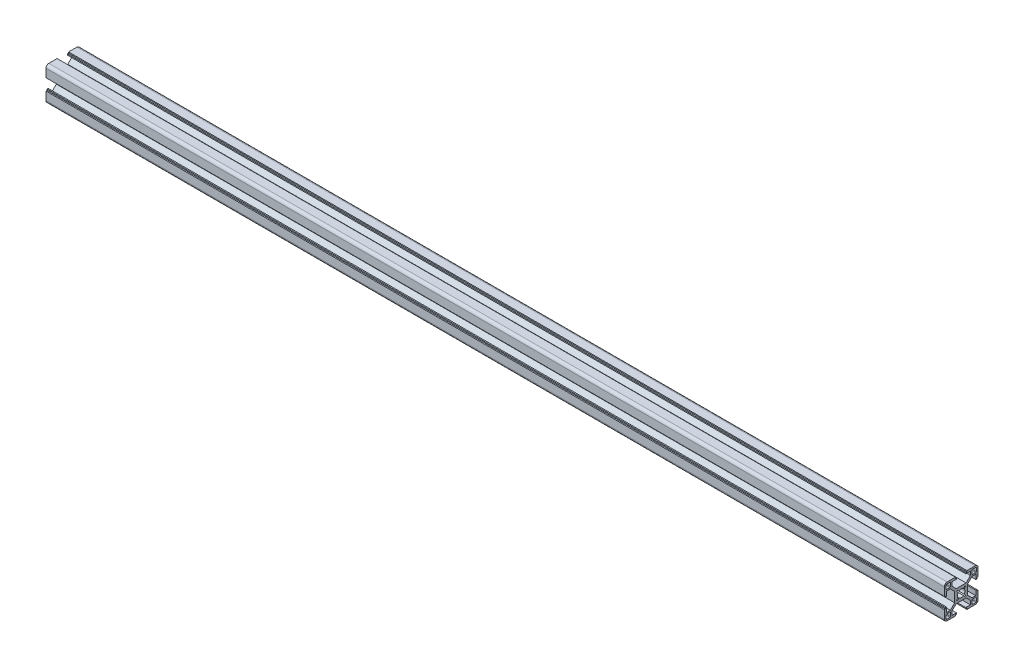
SolidWorks part; units mm, degrees
ref_plane "前视基准面" through (0, 0, 0) normal (0, 0, 1) x (1, 0, 0)
ref_plane "上视基准面" through (0, 0, 0) normal (0, 1, 0) x (1, 0, 0)
ref_plane "右视基准面" through (0, 0, 0) normal (1, 0, 0) x (0, 0, -1)
other "Configuration Table"
sketch "草图1" plane through (0, 0, 0) normal (1, 0, 0) x (0, 0, -1)
  line L0 (-5.1496, -13.7047) -> (-4.1496, -13.7047)
  line L1 (-4.1496, -13.7047) -> (-4.1496, -12.7047)
  line L2 (-4.1496, -12.7047) -> (-8.2996, -12.7047)
  line L3 (-8.2996, -12.7047) -> (-8.2996, -9.3689)
  line L4 (-8.2996, -9.3689) -> (-4.4354, -5.5047)
  line L5 (-4.4354, -5.5047) -> (4.3362, -5.5047)
  line L6 (4.3362, -5.5047) -> (8.2004, -9.3689)
  line L7 (8.2004, -9.3689) -> (8.2004, -12.7047)
  line L8 (8.2004, -12.7047) -> (4.0504, -12.7047)
  line L9 (4.0504, -12.7047) -> (4.0504, -13.7047)
  line L10 (4.0504, -13.7047) -> (5.0504, -13.7047)
  line L11 (5.0504, -13.7047) -> (5.0504, -14.7047)
  line L12 (5.0504, -14.7047) -> (12.4504, -14.7047)
  line L13 (14.9504, -12.2047) -> (14.9504, -4.8047)
  line L14 (14.9504, -4.8047) -> (13.9504, -4.8047)
  line L15 (13.9504, -4.8047) -> (13.9504, -3.8047)
  line L16 (13.9504, -3.8047) -> (12.9504, -3.8047)
  line L17 (12.9504, -3.8047) -> (12.9504, -7.9547)
  line L18 (12.9504, -7.9547) -> (9.6146, -7.9547)
  line L19 (9.6146, -7.9547) -> (5.7504, -4.0905)
  line L20 (5.7504, -4.0905) -> (5.7504, 4.6811)
  line L21 (5.7504, 4.6811) -> (9.6146, 8.5453)
  line L22 (9.6146, 8.5453) -> (12.9504, 8.5453)
  line L23 (12.9504, 8.5453) -> (12.9504, 4.3953)
  line L24 (12.9504, 4.3953) -> (13.9504, 4.3953)
  line L25 (13.9504, 4.3953) -> (13.9504, 5.3953)
  line L26 (13.9504, 5.3953) -> (14.9504, 5.3953)
  line L27 (14.9504, 5.3953) -> (14.9504, 12.7953)
  line L28 (12.4504, 15.2953) -> (5.0504, 15.2953)
  line L29 (5.0504, 15.2953) -> (5.0504, 14.2953)
  line L30 (5.0504, 14.2953) -> (4.0504, 14.2953)
  line L31 (4.0504, 14.2953) -> (4.0504, 13.2953)
  line L32 (4.0504, 13.2953) -> (8.2004, 13.2953)
  line L33 (8.2004, 13.2953) -> (8.2004, 9.9595)
  line L34 (8.2004, 9.9595) -> (4.3362, 6.0953)
  line L35 (4.3362, 6.0953) -> (-4.4354, 6.0953)
  line L36 (-4.4354, 6.0953) -> (-8.2996, 9.9595)
  line L37 (-8.2996, 9.9595) -> (-8.2996, 13.2953)
  line L38 (-8.2996, 13.2953) -> (-4.1496, 13.2953)
  line L39 (-4.1496, 13.2953) -> (-4.1496, 14.2953)
  line L40 (-4.1496, 14.2953) -> (-5.1496, 14.2953)
  line L41 (-5.1496, 14.2953) -> (-5.1496, 15.2953)
  line L42 (-5.1496, 15.2953) -> (-12.5496, 15.2953)
  line L43 (-15.0496, 12.7953) -> (-15.0496, 5.3953)
  line L44 (-15.0496, 5.3953) -> (-14.0496, 5.3953)
  line L45 (-14.0496, 5.3953) -> (-14.0496, 4.3953)
  line L46 (-14.0496, 4.3953) -> (-13.0496, 4.3953)
  line L47 (-13.0496, 4.3953) -> (-13.0496, 8.5453)
  line L48 (-13.0496, 8.5453) -> (-9.7138, 8.5453)
  line L49 (-9.7138, 8.5453) -> (-5.8496, 4.6811)
  line L50 (-5.8496, 4.6811) -> (-5.8496, -4.0905)
  line L51 (-5.8496, -4.0905) -> (-9.7138, -7.9547)
  line L52 (-9.7138, -7.9547) -> (-13.0496, -7.9547)
  line L53 (-13.0496, -7.9547) -> (-13.0496, -3.8047)
  line L54 (-13.0496, -3.8047) -> (-14.0496, -3.8047)
  line L55 (-14.0496, -3.8047) -> (-14.0496, -4.8047)
  line L56 (-14.0496, -4.8047) -> (-15.0496, -4.8047)
  line L57 (-15.0496, -4.8047) -> (-15.0496, -12.2047)
  line L58 (-12.5496, -14.7047) -> (-5.1496, -14.7047)
  line L59 (-5.1496, -14.7047) -> (-5.1496, -13.7047)
  line L60 (-10.0496, 9.7953) -> (-13.0496, 9.7953)
  line L61 (-13.5496, 10.2953) -> (-13.5496, 13.2953)
  line L62 (-13.0496, 13.7953) -> (-10.0496, 13.7953)
  line L63 (-9.5496, 13.2953) -> (-9.5496, 10.2953)
  line L64 (-10.0496, -13.2047) -> (-13.0496, -13.2047)
  line L65 (-13.5496, -12.7047) -> (-13.5496, -9.7047)
  line L66 (-13.0496, -9.2047) -> (-10.0496, -9.2047)
  line L67 (-9.5496, -9.7047) -> (-9.5496, -12.7047)
  line L68 (12.9504, 9.7953) -> (9.9504, 9.7953)
  line L69 (9.4504, 10.2953) -> (9.4504, 13.2953)
  line L70 (9.9504, 13.7953) -> (12.9504, 13.7953)
  line L71 (13.4504, 13.2953) -> (13.4504, 10.2953)
  line L72 (13.4504, -9.7047) -> (13.4504, -12.7047)
  line L73 (12.9504, -13.2047) -> (9.9504, -13.2047)
  line L74 (9.4504, -12.7047) -> (9.4504, -9.7047)
  line L75 (9.9504, -9.2047) -> (12.9504, -9.2047)
  line L76 (-4.08, 3.6186) -> (-3.3729, 4.3257)
  line L77 (-3.3729, 4.3257) -> (-2.074, 3.0269)
  line L78 (1.9749, 3.0269) -> (3.2737, 4.3257)
  line L79 (3.2737, 4.3257) -> (3.9808, 3.6186)
  line L80 (3.9808, 3.6186) -> (2.682, 2.3198)
  line L81 (2.682, -1.7291) -> (3.9808, -3.028)
  line L82 (3.9808, -3.028) -> (3.2737, -3.7351)
  line L83 (3.2737, -3.7351) -> (1.9749, -2.4362)
  line L84 (-2.074, -2.4362) -> (-3.3729, -3.7351)
  line L85 (-3.3729, -3.7351) -> (-4.08, -3.028)
  line L86 (-4.08, -3.028) -> (-2.7811, -1.7291)
  line L87 (-2.7811, 2.3198) -> (-4.08, 3.6186)
  arc A0 (12.4504, -14.7047) -> (14.9504, -12.2047) centre (12.4504, -12.2047) ccw
  arc A1 (14.9504, 12.7953) -> (12.4504, 15.2953) centre (12.4504, 12.7953) ccw
  arc A2 (-12.5496, 15.2953) -> (-15.0496, 12.7953) centre (-12.5496, 12.7953) ccw
  arc A3 (-15.0496, -12.2047) -> (-12.5496, -14.7047) centre (-12.5496, -12.2047) ccw
  arc A4 (-9.5496, 10.2953) -> (-10.0496, 9.7953) centre (-10.0496, 10.2953) cw
  arc A5 (-13.0496, 9.7953) -> (-13.5496, 10.2953) centre (-13.0496, 10.2953) cw
  arc A6 (-13.5496, 13.2953) -> (-13.0496, 13.7953) centre (-13.0496, 13.2953) cw
  arc A7 (-10.0496, 13.7953) -> (-9.5496, 13.2953) centre (-10.0496, 13.2953) cw
  arc A8 (-9.5496, -12.7047) -> (-10.0496, -13.2047) centre (-10.0496, -12.7047) cw
  arc A9 (-13.0496, -13.2047) -> (-13.5496, -12.7047) centre (-13.0496, -12.7047) cw
  arc A10 (-13.5496, -9.7047) -> (-13.0496, -9.2047) centre (-13.0496, -9.7047) cw
  arc A11 (-10.0496, -9.2047) -> (-9.5496, -9.7047) centre (-10.0496, -9.7047) cw
  arc A12 (13.4504, 10.2953) -> (12.9504, 9.7953) centre (12.9504, 10.2953) cw
  arc A13 (9.9504, 9.7953) -> (9.4504, 10.2953) centre (9.9504, 10.2953) cw
  arc A14 (9.4504, 13.2953) -> (9.9504, 13.7953) centre (9.9504, 13.2953) cw
  arc A15 (12.9504, 13.7953) -> (13.4504, 13.2953) centre (12.9504, 13.2953) cw
  arc A16 (12.9504, -9.2047) -> (13.4504, -9.7047) centre (12.9504, -9.7047) cw
  arc A17 (13.4504, -12.7047) -> (12.9504, -13.2047) centre (12.9504, -12.7047) cw
  arc A18 (9.9504, -13.2047) -> (9.4504, -12.7047) centre (9.9504, -12.7047) cw
  arc A19 (9.4504, -9.7047) -> (9.9504, -9.2047) centre (9.9504, -9.7047) cw
  arc A20 (-2.074, 3.0269) -> (1.9749, 3.0269) centre (-0.0496, 0.2953) cw
  arc A21 (2.682, 2.3198) -> (2.682, -1.7291) centre (-0.0496, 0.2953) cw
  arc A22 (1.9749, -2.4362) -> (-2.074, -2.4362) centre (-0.0496, 0.2953) cw
  arc A23 (-2.7811, -1.7291) -> (-2.7811, 2.3198) centre (-0.0496, 0.2953) cw
extrude "凸台-拉伸1" add sketch "草图1" against normal blind 50
sketch "草图2" plane through (0, 0, 0) normal (1, 0, 0) x (0, 0, -1)
  line L4 (-13.0496, 9.7953) -> (-10.0496, 9.7953)
  line L5 (-13.5496, 13.2953) -> (-13.5496, 10.2953)
  line L6 (-10.0496, 13.7953) -> (-13.0496, 13.7953)
  line L7 (-9.5496, 10.2953) -> (-9.5496, 13.2953)
  line L8 (-13.0496, 9.7953) -> (-10.0496, 9.7953)
  line L9 (-13.5496, 13.2953) -> (-13.5496, 10.2953)
  line L10 (-10.0496, 13.7953) -> (-13.0496, 13.7953)
  line L11 (-9.5496, 10.2953) -> (-9.5496, 13.2953)
  line L12 (-13.0496, -13.2047) -> (-10.0496, -13.2047)
  line L13 (-13.5496, -9.7047) -> (-13.5496, -12.7047)
  line L14 (-10.0496, -9.2047) -> (-13.0496, -9.2047)
  line L15 (-9.5496, -12.7047) -> (-9.5496, -9.7047)
  line L16 (-13.0496, -13.2047) -> (-10.0496, -13.2047)
  line L17 (-13.5496, -9.7047) -> (-13.5496, -12.7047)
  line L18 (-10.0496, -9.2047) -> (-13.0496, -9.2047)
  line L19 (-9.5496, -12.7047) -> (-9.5496, -9.7047)
  line L20 (9.4504, 13.2953) -> (9.4504, 10.2953)
  line L21 (12.9504, 13.7953) -> (9.9504, 13.7953)
  line L22 (13.4504, 10.2953) -> (13.4504, 13.2953)
  line L23 (9.9504, 9.7953) -> (12.9504, 9.7953)
  line L24 (9.4504, 13.2953) -> (9.4504, 10.2953)
  line L25 (12.9504, 13.7953) -> (9.9504, 13.7953)
  line L26 (13.4504, 10.2953) -> (13.4504, 13.2953)
  line L27 (9.9504, 9.7953) -> (12.9504, 9.7953)
  line L28 (9.4504, -9.7047) -> (9.4504, -12.7047)
  line L29 (12.9504, -9.2047) -> (9.9504, -9.2047)
  line L30 (13.4504, -12.7047) -> (13.4504, -9.7047)
  line L31 (9.9504, -13.2047) -> (12.9504, -13.2047)
  line L32 (9.4504, -9.7047) -> (9.4504, -12.7047)
  line L33 (12.9504, -9.2047) -> (9.9504, -9.2047)
  line L34 (13.4504, -12.7047) -> (13.4504, -9.7047)
  line L35 (9.9504, -13.2047) -> (12.9504, -13.2047)
  line L44 (-3.3729, -3.7351) -> (-2.074, -2.4362)
  line L45 (-4.08, -3.028) -> (-3.3729, -3.7351)
  line L46 (-2.7811, -1.7291) -> (-4.08, -3.028)
  line L47 (-4.08, 3.6186) -> (-2.7811, 2.3198)
  line L48 (-3.3729, 4.3257) -> (-4.08, 3.6186)
  line L49 (-2.074, 3.0269) -> (-3.3729, 4.3257)
  line L50 (3.2737, 4.3257) -> (1.9749, 3.0269)
  line L51 (3.9808, 3.6186) -> (3.2737, 4.3257)
  line L52 (2.682, 2.3198) -> (3.9808, 3.6186)
  line L53 (3.9808, -3.028) -> (2.682, -1.7291)
  line L54 (3.2737, -3.7351) -> (3.9808, -3.028)
  line L55 (1.9749, -2.4362) -> (3.2737, -3.7351)
  line L56 (-3.3729, -3.7351) -> (-2.074, -2.4362)
  line L57 (-4.08, -3.028) -> (-3.3729, -3.7351)
  line L58 (-2.7811, -1.7291) -> (-4.08, -3.028)
  line L59 (-4.08, 3.6186) -> (-2.7811, 2.3198)
  line L60 (-3.3729, 4.3257) -> (-4.08, 3.6186)
  line L61 (-2.074, 3.0269) -> (-3.3729, 4.3257)
  line L62 (3.2737, 4.3257) -> (1.9749, 3.0269)
  line L63 (3.9808, 3.6186) -> (3.2737, 4.3257)
  line L64 (2.682, 2.3198) -> (3.9808, 3.6186)
  line L65 (3.9808, -3.028) -> (2.682, -1.7291)
  line L66 (3.2737, -3.7351) -> (3.9808, -3.028)
  line L67 (1.9749, -2.4362) -> (3.2737, -3.7351)
  line L68 (-15.0496, -4.8047) -> (-15.0496, -12.2047)
  line L69 (-14.0496, -4.8047) -> (-15.0496, -4.8047)
  line L70 (-14.0496, -3.8047) -> (-14.0496, -4.8047)
  line L71 (-13.0496, -3.8047) -> (-14.0496, -3.8047)
  line L72 (-13.0496, -7.9547) -> (-13.0496, -3.8047)
  line L73 (-9.7138, -7.9547) -> (-13.0496, -7.9547)
  line L74 (-5.8496, -4.0905) -> (-9.7138, -7.9547)
  line L75 (-5.8496, 4.6811) -> (-5.8496, -4.0905)
  line L76 (-9.7138, 8.5453) -> (-5.8496, 4.6811)
  line L77 (-13.0496, 8.5453) -> (-9.7138, 8.5453)
  line L78 (-13.0496, 4.3953) -> (-13.0496, 8.5453)
  line L79 (-14.0496, 4.3953) -> (-13.0496, 4.3953)
  line L80 (-14.0496, 5.3953) -> (-14.0496, 4.3953)
  line L81 (-15.0496, 5.3953) -> (-14.0496, 5.3953)
  line L82 (-15.0496, 12.7953) -> (-15.0496, 5.3953)
  line L83 (-5.1496, 15.2953) -> (-12.5496, 15.2953)
  line L84 (-5.1496, 14.2953) -> (-5.1496, 15.2953)
  line L85 (-4.1496, 14.2953) -> (-5.1496, 14.2953)
  line L86 (-4.1496, 13.2953) -> (-4.1496, 14.2953)
  line L87 (-8.2996, 13.2953) -> (-4.1496, 13.2953)
  line L88 (-8.2996, 9.9595) -> (-8.2996, 13.2953)
  line L89 (-4.4354, 6.0953) -> (-8.2996, 9.9595)
  line L90 (4.3362, 6.0953) -> (-4.4354, 6.0953)
  line L91 (8.2004, 9.9595) -> (4.3362, 6.0953)
  line L92 (8.2004, 13.2953) -> (8.2004, 9.9595)
  line L93 (4.0504, 13.2953) -> (8.2004, 13.2953)
  line L94 (4.0504, 14.2953) -> (4.0504, 13.2953)
  line L95 (5.0504, 14.2953) -> (4.0504, 14.2953)
  line L96 (5.0504, 15.2953) -> (5.0504, 14.2953)
  line L97 (12.4504, 15.2953) -> (5.0504, 15.2953)
  line L98 (14.9504, 5.3953) -> (14.9504, 12.7953)
  line L99 (13.9504, 5.3953) -> (14.9504, 5.3953)
  line L100 (13.9504, 4.3953) -> (13.9504, 5.3953)
  line L101 (12.9504, 4.3953) -> (13.9504, 4.3953)
  line L102 (12.9504, 8.5453) -> (12.9504, 4.3953)
  line L103 (9.6146, 8.5453) -> (12.9504, 8.5453)
  line L104 (5.7504, 4.6811) -> (9.6146, 8.5453)
  line L105 (5.7504, -4.0905) -> (5.7504, 4.6811)
  line L106 (9.6146, -7.9547) -> (5.7504, -4.0905)
  line L107 (12.9504, -7.9547) -> (9.6146, -7.9547)
  line L108 (12.9504, -3.8047) -> (12.9504, -7.9547)
  line L109 (13.9504, -3.8047) -> (12.9504, -3.8047)
  line L110 (13.9504, -4.8047) -> (13.9504, -3.8047)
  line L111 (14.9504, -4.8047) -> (13.9504, -4.8047)
  line L112 (14.9504, -12.2047) -> (14.9504, -4.8047)
  line L113 (5.0504, -14.7047) -> (12.4504, -14.7047)
  line L114 (5.0504, -13.7047) -> (5.0504, -14.7047)
  line L115 (4.0504, -13.7047) -> (5.0504, -13.7047)
  line L116 (4.0504, -12.7047) -> (4.0504, -13.7047)
  line L117 (8.2004, -12.7047) -> (4.0504, -12.7047)
  line L118 (8.2004, -9.3689) -> (8.2004, -12.7047)
  line L119 (4.3362, -5.5047) -> (8.2004, -9.3689)
  line L120 (-4.4354, -5.5047) -> (4.3362, -5.5047)
  line L121 (-8.2996, -9.3689) -> (-4.4354, -5.5047)
  line L122 (-8.2996, -12.7047) -> (-8.2996, -9.3689)
  line L123 (-4.1496, -12.7047) -> (-8.2996, -12.7047)
  line L124 (-4.1496, -13.7047) -> (-4.1496, -12.7047)
  line L125 (-5.1496, -13.7047) -> (-4.1496, -13.7047)
  line L126 (-5.1496, -14.7047) -> (-5.1496, -13.7047)
  line L127 (-12.5496, -14.7047) -> (-5.1496, -14.7047)
  line L128 (-15.0496, -4.8047) -> (-15.0496, -12.2047)
  line L129 (-14.0496, -4.8047) -> (-15.0496, -4.8047)
  line L130 (-14.0496, -3.8047) -> (-14.0496, -4.8047)
  line L131 (-13.0496, -3.8047) -> (-14.0496, -3.8047)
  line L132 (-13.0496, -7.9547) -> (-13.0496, -3.8047)
  line L133 (-9.7138, -7.9547) -> (-13.0496, -7.9547)
  line L134 (-5.8496, -4.0905) -> (-9.7138, -7.9547)
  line L135 (-5.8496, 4.6811) -> (-5.8496, -4.0905)
  line L136 (-9.7138, 8.5453) -> (-5.8496, 4.6811)
  line L137 (-13.0496, 8.5453) -> (-9.7138, 8.5453)
  line L138 (-13.0496, 4.3953) -> (-13.0496, 8.5453)
  line L139 (-14.0496, 4.3953) -> (-13.0496, 4.3953)
  line L140 (-14.0496, 5.3953) -> (-14.0496, 4.3953)
  line L141 (-15.0496, 5.3953) -> (-14.0496, 5.3953)
  line L142 (-15.0496, 12.7953) -> (-15.0496, 5.3953)
  line L143 (-5.1496, 15.2953) -> (-12.5496, 15.2953)
  line L144 (-5.1496, 14.2953) -> (-5.1496, 15.2953)
  line L145 (-4.1496, 14.2953) -> (-5.1496, 14.2953)
  line L146 (-4.1496, 13.2953) -> (-4.1496, 14.2953)
  line L147 (-8.2996, 13.2953) -> (-4.1496, 13.2953)
  line L148 (-8.2996, 9.9595) -> (-8.2996, 13.2953)
  line L149 (-4.4354, 6.0953) -> (-8.2996, 9.9595)
  line L150 (4.3362, 6.0953) -> (-4.4354, 6.0953)
  line L151 (8.2004, 9.9595) -> (4.3362, 6.0953)
  line L152 (8.2004, 13.2953) -> (8.2004, 9.9595)
  line L153 (4.0504, 13.2953) -> (8.2004, 13.2953)
  line L154 (4.0504, 14.2953) -> (4.0504, 13.2953)
  line L155 (5.0504, 14.2953) -> (4.0504, 14.2953)
  line L156 (5.0504, 15.2953) -> (5.0504, 14.2953)
  line L157 (12.4504, 15.2953) -> (5.0504, 15.2953)
  line L158 (14.9504, 5.3953) -> (14.9504, 12.7953)
  line L159 (13.9504, 5.3953) -> (14.9504, 5.3953)
  line L160 (13.9504, 4.3953) -> (13.9504, 5.3953)
  line L161 (12.9504, 4.3953) -> (13.9504, 4.3953)
  line L162 (12.9504, 8.5453) -> (12.9504, 4.3953)
  line L163 (9.6146, 8.5453) -> (12.9504, 8.5453)
  line L164 (5.7504, 4.6811) -> (9.6146, 8.5453)
  line L165 (5.7504, -4.0905) -> (5.7504, 4.6811)
  line L166 (9.6146, -7.9547) -> (5.7504, -4.0905)
  line L167 (12.9504, -7.9547) -> (9.6146, -7.9547)
  line L168 (12.9504, -3.8047) -> (12.9504, -7.9547)
  line L169 (13.9504, -3.8047) -> (12.9504, -3.8047)
  line L170 (13.9504, -4.8047) -> (13.9504, -3.8047)
  line L171 (14.9504, -4.8047) -> (13.9504, -4.8047)
  line L172 (14.9504, -12.2047) -> (14.9504, -4.8047)
  line L173 (5.0504, -14.7047) -> (12.4504, -14.7047)
  line L174 (5.0504, -13.7047) -> (5.0504, -14.7047)
  line L175 (4.0504, -13.7047) -> (5.0504, -13.7047)
  line L176 (4.0504, -12.7047) -> (4.0504, -13.7047)
  line L177 (8.2004, -12.7047) -> (4.0504, -12.7047)
  line L178 (8.2004, -9.3689) -> (8.2004, -12.7047)
  line L179 (4.3362, -5.5047) -> (8.2004, -9.3689)
  line L180 (-4.4354, -5.5047) -> (4.3362, -5.5047)
  line L181 (-8.2996, -9.3689) -> (-4.4354, -5.5047)
  line L182 (-8.2996, -12.7047) -> (-8.2996, -9.3689)
  line L183 (-4.1496, -12.7047) -> (-8.2996, -12.7047)
  line L184 (-4.1496, -13.7047) -> (-4.1496, -12.7047)
  line L185 (-5.1496, -13.7047) -> (-4.1496, -13.7047)
  line L186 (-5.1496, -14.7047) -> (-5.1496, -13.7047)
  line L187 (-12.5496, -14.7047) -> (-5.1496, -14.7047)
  arc A4 (-13.5496, 10.2953) -> (-13.0496, 9.7953) centre (-13.0496, 10.2953) ccw
  arc A5 (-13.0496, 13.7953) -> (-13.5496, 13.2953) centre (-13.0496, 13.2953) ccw
  arc A6 (-9.5496, 13.2953) -> (-10.0496, 13.7953) centre (-10.0496, 13.2953) ccw
  arc A7 (-10.0496, 9.7953) -> (-9.5496, 10.2953) centre (-10.0496, 10.2953) ccw
  arc A8 (-13.5496, 10.2953) -> (-13.0496, 9.7953) centre (-13.0496, 10.2953) ccw
  arc A9 (-13.0496, 13.7953) -> (-13.5496, 13.2953) centre (-13.0496, 13.2953) ccw
  arc A10 (-9.5496, 13.2953) -> (-10.0496, 13.7953) centre (-10.0496, 13.2953) ccw
  arc A11 (-10.0496, 9.7953) -> (-9.5496, 10.2953) centre (-10.0496, 10.2953) ccw
  arc A12 (-12.5496, 15.2953) -> (-15.0496, 12.7953) centre (-12.5496, 12.7953) ccw
  arc A13 (14.9504, 12.7953) -> (12.4504, 15.2953) centre (12.4504, 12.7953) ccw
  arc A14 (12.4504, -14.7047) -> (14.9504, -12.2047) centre (12.4504, -12.2047) ccw
  arc A15 (-15.0496, -12.2047) -> (-12.5496, -14.7047) centre (-12.5496, -12.2047) ccw
  arc A16 (-12.5496, 15.2953) -> (-15.0496, 12.7953) centre (-12.5496, 12.7953) ccw
  arc A17 (14.9504, 12.7953) -> (12.4504, 15.2953) centre (12.4504, 12.7953) ccw
  arc A18 (12.4504, -14.7047) -> (14.9504, -12.2047) centre (12.4504, -12.2047) ccw
  arc A19 (-15.0496, -12.2047) -> (-12.5496, -14.7047) centre (-12.5496, -12.2047) ccw
  arc A20 (-13.5496, -12.7047) -> (-13.0496, -13.2047) centre (-13.0496, -12.7047) ccw
  arc A21 (-13.0496, -9.2047) -> (-13.5496, -9.7047) centre (-13.0496, -9.7047) ccw
  arc A22 (-9.5496, -9.7047) -> (-10.0496, -9.2047) centre (-10.0496, -9.7047) ccw
  arc A23 (-10.0496, -13.2047) -> (-9.5496, -12.7047) centre (-10.0496, -12.7047) ccw
  arc A24 (-13.5496, -12.7047) -> (-13.0496, -13.2047) centre (-13.0496, -12.7047) ccw
  arc A25 (-13.0496, -9.2047) -> (-13.5496, -9.7047) centre (-13.0496, -9.7047) ccw
  arc A26 (-9.5496, -9.7047) -> (-10.0496, -9.2047) centre (-10.0496, -9.7047) ccw
  arc A27 (-10.0496, -13.2047) -> (-9.5496, -12.7047) centre (-10.0496, -12.7047) ccw
  arc A28 (9.9504, 13.7953) -> (9.4504, 13.2953) centre (9.9504, 13.2953) ccw
  arc A29 (13.4504, 13.2953) -> (12.9504, 13.7953) centre (12.9504, 13.2953) ccw
  arc A30 (12.9504, 9.7953) -> (13.4504, 10.2953) centre (12.9504, 10.2953) ccw
  arc A31 (9.4504, 10.2953) -> (9.9504, 9.7953) centre (9.9504, 10.2953) ccw
  arc A32 (9.9504, 13.7953) -> (9.4504, 13.2953) centre (9.9504, 13.2953) ccw
  arc A33 (13.4504, 13.2953) -> (12.9504, 13.7953) centre (12.9504, 13.2953) ccw
  arc A34 (12.9504, 9.7953) -> (13.4504, 10.2953) centre (12.9504, 10.2953) ccw
  arc A35 (9.4504, 10.2953) -> (9.9504, 9.7953) centre (9.9504, 10.2953) ccw
  arc A36 (9.9504, -9.2047) -> (9.4504, -9.7047) centre (9.9504, -9.7047) ccw
  arc A37 (13.4504, -9.7047) -> (12.9504, -9.2047) centre (12.9504, -9.7047) ccw
  arc A38 (12.9504, -13.2047) -> (13.4504, -12.7047) centre (12.9504, -12.7047) ccw
  arc A39 (9.4504, -12.7047) -> (9.9504, -13.2047) centre (9.9504, -12.7047) ccw
  arc A40 (9.9504, -9.2047) -> (9.4504, -9.7047) centre (9.9504, -9.7047) ccw
  arc A41 (13.4504, -9.7047) -> (12.9504, -9.2047) centre (12.9504, -9.7047) ccw
  arc A42 (12.9504, -13.2047) -> (13.4504, -12.7047) centre (12.9504, -12.7047) ccw
  arc A43 (9.4504, -12.7047) -> (9.9504, -13.2047) centre (9.9504, -12.7047) ccw
  arc A44 (-2.7811, 2.3198) -> (-2.7811, -1.7291) centre (-0.0496, 0.2953) ccw
  arc A45 (1.9749, 3.0269) -> (-2.074, 3.0269) centre (-0.0496, 0.2953) ccw
  arc A46 (2.682, -1.7291) -> (2.682, 2.3198) centre (-0.0496, 0.2953) ccw
  arc A47 (-2.074, -2.4362) -> (1.9749, -2.4362) centre (-0.0496, 0.2953) ccw
  arc A48 (-2.7811, 2.3198) -> (-2.7811, -1.7291) centre (-0.0496, 0.2953) ccw
  arc A49 (1.9749, 3.0269) -> (-2.074, 3.0269) centre (-0.0496, 0.2953) ccw
  arc A50 (2.682, -1.7291) -> (2.682, 2.3198) centre (-0.0496, 0.2953) ccw
  arc A51 (-2.074, -2.4362) -> (1.9749, -2.4362) centre (-0.0496, 0.2953) ccw
  dimension "D1" = 0
  dimension "D2" = 0
  dimension "D3" = 0
  dimension "D4" = 0
  dimension "D5" = 0
  dimension "D6" = 0
extrude "凸台-拉伸2" add sketch "草图2" against normal blind 800
sketch "草图3" plane through (0, 0, 0) normal (0, 0, 1) x (1, 0, 0)
  line L0 (-1000, 0) -> (49000, 0) construction
  line L1 (-400, -1000.4802) -> (-400, 48999.5198) construction
  line L2 (-800, 4.6811) -> (-800, -4.0905) construction
  circle A0 centre (-755, 0) radius 3
  circle A1 centre (-45, 0) radius 3
  dimension "D2" = 6
  dimension "D1" = 400
  dimension "D3" = 45
extrude "切除-拉伸1" cut sketch "草图3" against normal up to surface (30 mm away) from surface at 15.0496 up to face at (-400, 9.0953, -14.9504) starting at face at (-400, -8.5047, 15.0496)
sketch "草图4" plane through (0, 0, 0) normal (0, 0, 1) x (1, 0, 0)
  line L0 (-1000, 0) -> (49000, 0) construction
  line L1 (-400, -1000) -> (-400, 49000) construction
  line L2 (-400, 0) -> (-475, 0) construction
  line L3 (-501.8, 0) -> (-448.2, 0) construction
  circle A0 centre (-501.8, 0) radius 3
  circle A1 centre (-448.2, 0) radius 3
  circle A2 centre (-351.8, 0) radius 3
  circle A3 centre (-298.2, 0) radius 3
  point P10 (-475, 0)
  dimension "D4" = 6
  dimension "D5" = 6
  dimension "D1" = 400
  dimension "D2" = 75
  dimension "D3" = 53.6
extrude "切除-拉伸2" cut sketch "草图4" along normal up to surface (30 mm away) from surface at -14.9504 up to face at (-400, 9.0953, 15.0496) starting at face at (-400, 9.0953, -14.9504)
